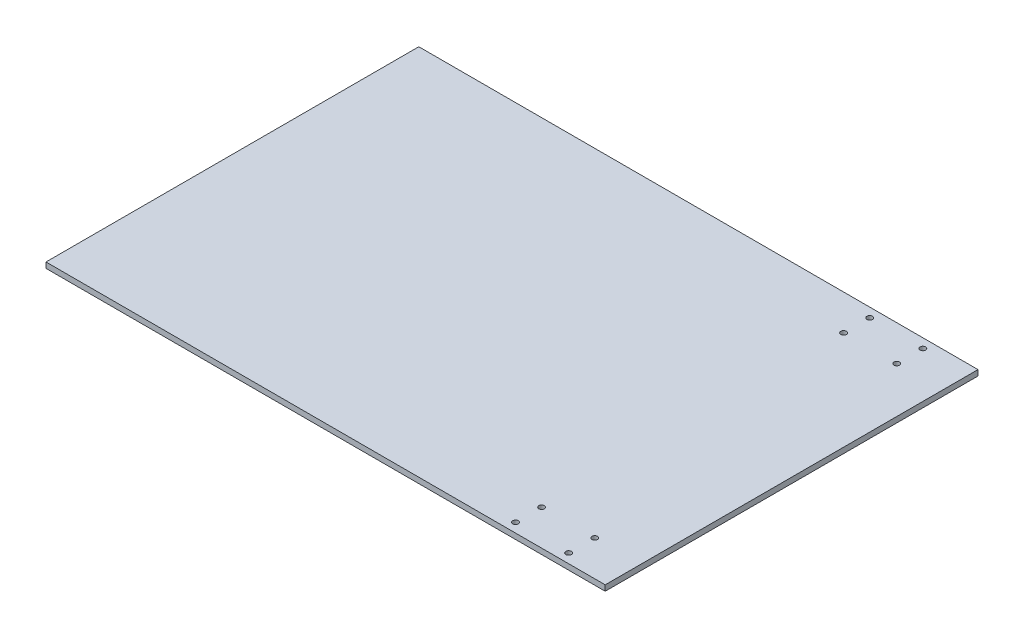
SolidWorks part; units mm, degrees
ref_plane "Front Plane" through (0, 0, 0) normal (0, 0, 1) x (1, 0, 0)
ref_plane "Top Plane" through (0, 0, 0) normal (0, 1, 0) x (1, 0, 0)
ref_plane "Right Plane" through (0, 0, 0) normal (1, 0, 0) x (0, 0, -1)
sketch "Sketch2" plane through (0, 0, 0) normal (0, 1, 0) x (1, 0, 0)
  line L1 (0, 0) -> (300, 0)
  line L2 (0, 0) -> (0, 200)
  line L3 (0, 200) -> (300, 200)
  line L4 (300, 0) -> (300, 200)
  dimension "D1" = 300
  dimension "D2" = 200
extrude "Boss-Extrude1" add sketch "Sketch2" along normal blind 3
sketch "Sketch3" plane through (0, 3, 0) normal (0, 1, 0) x (1, 0, 0)
  line L0 (300, 0) -> (300, 200) construction
  line L2 (150, 200) -> (150, 0) construction
  line L3 (300, 200) -> (0, 200) construction
  line L4 (0, 0) -> (300, 0) construction
  line L5 (0, 100) -> (300, 100) construction
  line L6 (0, 200) -> (0, 0) construction
  line L7 (300, 0) -> (300, 200) construction
  line L8 (300, 200) -> (0, 200) construction
  circle A1 centre (275.4, 195) radius 1.5
  circle A2 centre (246.9, 195) radius 1.5
  circle A3 centre (275.4, 181) radius 1.5
  circle A4 centre (246.9, 181) radius 1.5
  circle A5 centre (275.4, 19) radius 1.5
  circle A6 centre (275.4, 5) radius 1.5
  circle A7 centre (246.9, 5) radius 1.5
  circle A8 centre (246.9, 19) radius 1.5
  dimension "D1" = 3
  dimension "D2" = 3
  dimension "D3" = 3
  dimension "D4" = 3
  dimension "D5" = 5
  dimension "D6" = 24.6
  dimension "D7" = 14
  dimension "D8" = 24.6
  dimension "D9" = 28.5
  dimension "D10" = 5
  dimension "D11" = 14
  dimension "D12" = 28.5
extrude "Cut-Extrude1" cut sketch "Sketch3" against normal through all
